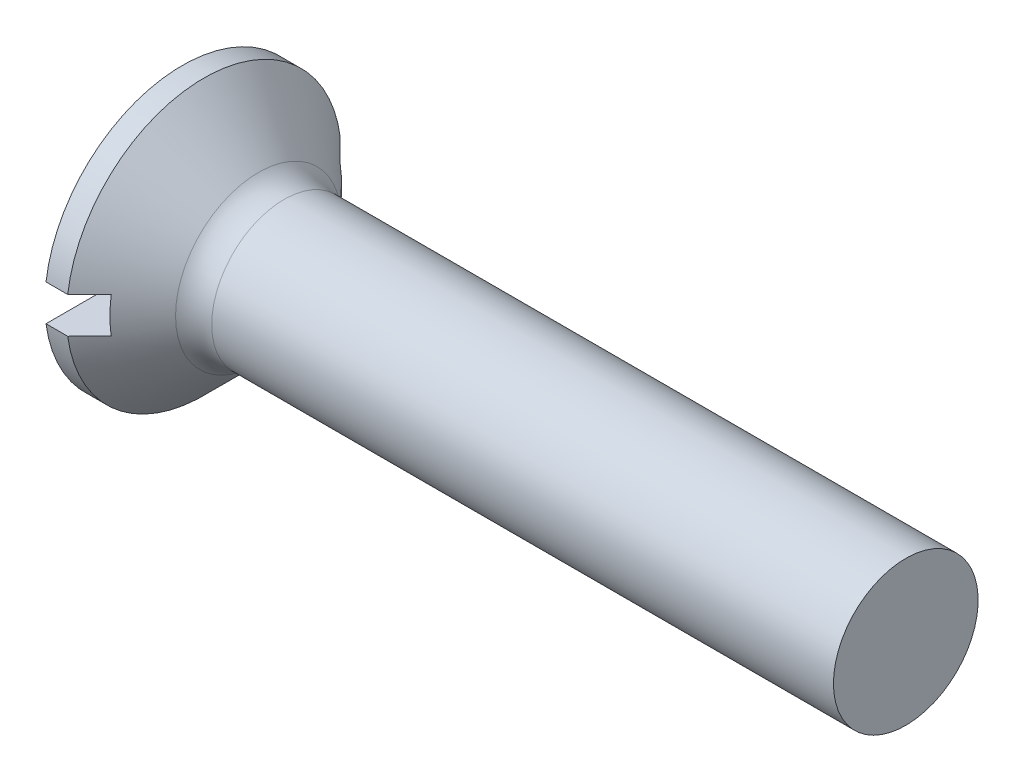
SolidWorks part; units mm, degrees
revolve "Base-Revolve" add sketch "BodySke" angle 360 about L5
sketch "BodySke" plane through (0, 0, 0) normal (0, 0, 1) x (1, 0, 0)
  line L0 (0, 0) -> (0, 1.9)
  line L1 (0, 1.9) -> (0.3, 1.9)
  line L2 (1.2, 1) -> (10, 1)
  line L3 (10, 1) -> (10, 0)
  line L4 (10, 0) -> (0, 0)
  line L5 (-6.35, 0) -> (82.55, 0) construction
  line L6 (1.2, -1) -> (10, -1) construction
  line L7 (0.3, -1.9) -> (1.2, -1) construction
  line L8 (0.3, 1.9) -> (1.2, 1)
  line L9 (0, -1.9) -> (0.3, -1.9) construction
  line L10 (1.6, 2.5875) -> (1.6, -6.9375) construction
  line L11 (0, 6.35) -> (0, -3.175) construction
  dimension "Diameter" = 2
  dimension "Length" = 10
  dimension "Head_ht" = 1.2
  dimension "Head_dia" = 3.8
  dimension "Head_ang" = 90
  dimension "D6" = 0.3
  dimension "Advance" = 0.4
  dimension "Thread_nom" = 10
cosmetic thread "ThreadCosmetic" [suppressed] parameters "Thread_length"=8.4, "Thread_minor"=1.548
extrude "Slot" cut sketch "Sketch2" against normal blind 0.6
sketch "Sketch2" plane through (0, 0, 0) normal (-1, 0, 0) x (0, 0, 1)
  line L0 (-1.9, -0.25) -> (1.9, -0.25)
  line L1 (-1.9, -0.25) -> (-1.9, 0.25)
  line L2 (1.9, 0.25) -> (-1.9, 0.25)
  line L3 (1.9, 0.25) -> (1.9, -0.25)
  dimension "Slot_width" = 0.5
  dimension "D1" = 0.25
  dimension "D2" = 3.8
  dimension "D3" = 1.9
ref_plane "Plane1" through (0, 0, 0) normal (0, 0, 1) x (1, 0, 0)
ref_plane "Plane2" through (0, 0, 0) normal (0, 1, 0) x (1, 0, 0)
ref_plane "Plane3" through (0, 0, 0) normal (1, 0, 0) x (0, 0, -1)
fillet "Fillet1" radius 0.5 1 edges at (1.2, 0, 1)
sketch "ThdSchSke" plane through (0, 0, 0) normal (0, 0, 1) x (1, 0, 0)
  line L0 (1.6, -0.774) -> (1.4418, -1)
  line L1 (1.6, -0.774) -> (1.7582, -1)
  line L2 (1.7582, -1) -> (1.7582, -1.25)
  line L3 (-3.175, 0) -> (5.1513, 0) construction
  line L5 (1.7582, -1.25) -> (1.4418, -1.25)
  line L6 (1.4418, -1.25) -> (1.4418, -1)
  line L7 (0, 1.9) -> (0, 0.25) construction
  dimension "Diameter" = 2
  dimension "Thread_minor" = 1.548
  dimension "Start" = 1.6
revolve "ThreadSchematic" [suppressed] cut sketch "ThdSchSke" angle 360 about L3
pattern_linear "ThdSchPat" [suppressed]
equation "\"D1@Sketch2\" = \"Slot_width@Sketch2\" / 2"
equation "\"D2@Sketch2\" = \"Head_dia@BodySke\""
equation "\"D3@Sketch2\" = \"D2@Sketch2\" / 2"
equation "\"Thread_length@ThreadCosmetic\" = ((sgn( (\"Length@BodySke\" - \"Advance@BodySke\" * 1.0 - \"Head_ht@BodySke\" ) - \"Thread_nom@BodySke\" )-1)*( (\"Length@BodySke\" - \"Advance@BodySke\" * 1.0 - \"Head_ht@BodySke\" ) - \"Thread_nom@BodySke\" ))/-2+ \"Thread_nom@BodySke\""
equation "\"Thread_minor@ThdSchSke\" = \"Thread_minor@ThreadCosmetic\""
equation "\"Diameter@ThdSchSke\" = \"Diameter@BodySke\""
equation "\"Overcut@ThdSchSke\" = \"Diameter@BodySke\" * 1.25"
equation "\"Start@ThdSchSke\" = 0.000001 + \"Length@BodySke\" - \"Thread_length@ThreadCosmetic\"  '---Countersunk---"
equation "\"Num_threads@ThdSchPat\" = int( \"Thread_length@ThreadCosmetic\" / \"Advance@BodySke\" + 0.999 )  + 1"
equation "\"Advance@ThdSchPat\" = \"Thread_length@ThreadCosmetic\" /  (\"Num_threads@ThdSchPat\" - 1) 'relax it"
